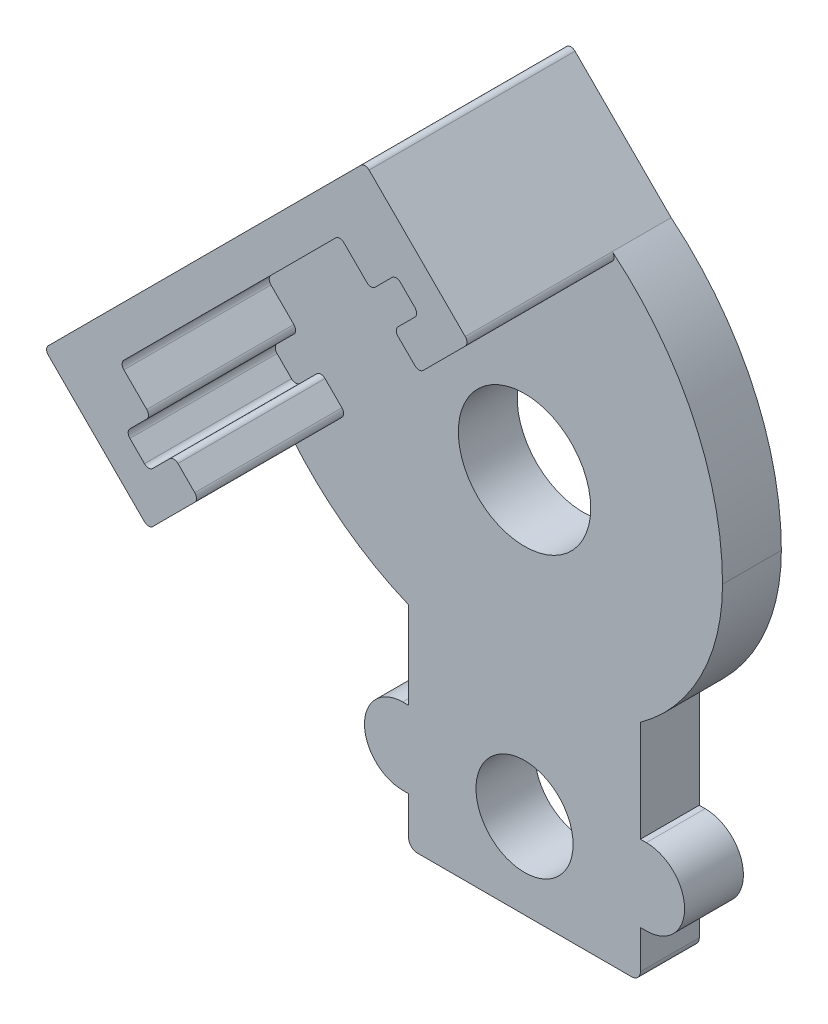
SolidWorks part; units mm, degrees
ref_plane "Front Plane" through (0, 0, 0) normal (0, 0, 1) x (1, 0, 0)
ref_plane "Top Plane" through (0, 0, 0) normal (0, 1, 0) x (1, 0, 0)
ref_plane "Right Plane" through (0, 0, 0) normal (1, 0, 0) x (0, 0, -1)
sketch "Sketch1" plane through (0, 0, 0) normal (0, 0, 1) x (1, 0, 0)
  line L39 (-4.14, -8.9) -> (-3.94, -8.9)
  line L40 (3.64, -13.1) -> (-3.64, -13.1)
  line L41 (3.94, -8.9) -> (4.14, -8.9)
  line L56 (3.94, -12.8) -> (3.94, -11.5)
  line L57 (-3.94, -12.8) -> (-3.94, -11.5)
  line L67 (-7.9196, -2.984) -> (-11.1864, 0.2828)
  line L68 (-0.5657, 11.1864) -> (-11.1864, 0.5657)
  line L69 (2.984, 7.9196) -> (-0.2828, 11.1864)
  line L70 (-4.14, -11.5) -> (-3.94, -11.5)
  line L71 (3.94, -11.5) -> (4.14, -11.5)
  line L72 (-3.94, -8.9) -> (-3.94, -5.942)
  line L75 (3.94, -8.9) -> (3.94, -5.4561)
  circle A16 centre (0, 0) radius 2.25
  arc A38 (-0.2828, 11.1864) -> (-0.5657, 11.1864) centre (-0.4243, 11.045) ccw
  arc A64 (-11.1864, 0.2828) -> (-11.1864, 0.5657) centre (-11.045, 0.4243) cw
  arc A66 (3.94, -5.4561) -> (6.73, 0) centre (0, 0) ccw
  arc A67 (-3.94, -5.942) -> (-7.9196, -2.984) centre (0, 3.5146) cw
  arc A68 (6.73, 0) -> (2.984, 7.9196) centre (-3.5146, 0) ccw
  circle A69 centre (0, -10.2) radius 1.65
  arc A70 (-4.14, -8.9) -> (-4.14, -11.5) centre (-4.14, -10.2) ccw
  arc A71 (4.14, -11.5) -> (4.14, -8.9) centre (4.14, -10.2) ccw
  arc A72 (-3.64, -13.1) -> (-3.94, -12.8) centre (-3.64, -12.8) cw
  arc A73 (3.64, -13.1) -> (3.94, -12.8) centre (3.64, -12.8) ccw
extrude "Boss-Extrude1" add sketch "Sketch1" along normal blind 2
sketch "Sketch2" plane through (0, 0, 2) normal (0, 0, 1) x (1, 0, 0)
  line L0 (0.7, 6.7812) -> (1.2728, 6.2084)
  line L1 (-6.7812, -0.7) -> (-6.2084, -1.2728)
  line L2 (-1.4213, 8.6196) -> (-8.6196, 1.4213)
  line L3 (-0.0778, 7.8418) -> (0.495, 8.4146)
  line L4 (1.2728, 7.9196) -> (0.7778, 8.4146)
  line L5 (-7.9196, -1.2728) -> (-8.4146, -0.7778)
  line L6 (-8.4146, -0.495) -> (-7.8418, 0.0778)
  line L7 (2.984, 7.6368) -> (1.5556, 6.2084)
  line L8 (1.2728, 7.6368) -> (0.7, 7.064)
  line L9 (-7.064, -0.7) -> (-7.6368, -1.2728)
  line L10 (-6.2084, -1.5556) -> (-7.6368, -2.984)
  line L12 (-7.9196, -2.984) -> (-11.1864, 0.2828)
  line L13 (-0.5657, 11.1864) -> (-11.1864, 0.5657)
  line L14 (2.984, 7.9196) -> (-0.2828, 11.1864)
  line L15 (-0.3606, 7.8418) -> (-1.1384, 8.6196)
  line L16 (-7.8418, 0.3606) -> (-8.6196, 1.1384)
  arc A1 (-0.2828, 11.1864) -> (-0.5657, 11.1864) centre (-0.4243, 11.045) ccw
  arc A2 (-7.6368, -1.2728) -> (-7.9196, -1.2728) centre (-7.7782, -1.1314) cw
  arc A3 (-8.4146, -0.495) -> (-8.4146, -0.7778) centre (-8.2731, -0.6364) ccw
  arc A4 (-7.8418, 0.0778) -> (-7.8418, 0.3606) centre (-7.9832, 0.2192) ccw
  arc A5 (1.2728, 7.6368) -> (1.2728, 7.9196) centre (1.1314, 7.7782) ccw
  arc A6 (0.495, 8.4146) -> (0.7778, 8.4146) centre (0.6364, 8.2731) cw
  arc A7 (-0.0778, 7.8418) -> (-0.3606, 7.8418) centre (-0.2192, 7.9832) cw
  arc A8 (-6.7812, -0.7) -> (-7.064, -0.7) centre (-6.9226, -0.8415) ccw
  arc A9 (0.7, 6.7812) -> (0.7, 7.064) centre (0.8415, 6.9226) cw
  arc A10 (-6.2084, -1.5556) -> (-6.2084, -1.2728) centre (-6.3498, -1.4142) ccw
  arc A11 (1.5556, 6.2084) -> (1.2728, 6.2084) centre (1.4142, 6.3498) cw
  arc A12 (-7.6368, -2.984) -> (-7.9196, -2.984) centre (-7.7782, -2.8426) cw
  arc A13 (2.984, 7.6368) -> (2.984, 7.9196) centre (2.8426, 7.7782) ccw
  arc A14 (-1.1384, 8.6196) -> (-1.4213, 8.6196) centre (-1.2799, 8.4782) ccw
  arc A15 (-8.6196, 1.1384) -> (-8.6196, 1.4213) centre (-8.4782, 1.2799) cw
  arc A16 (-11.1864, 0.2828) -> (-11.1864, 0.5657) centre (-11.045, 0.4243) cw
extrude "Boss-Extrude2" add sketch "Sketch2" along normal blind 5
